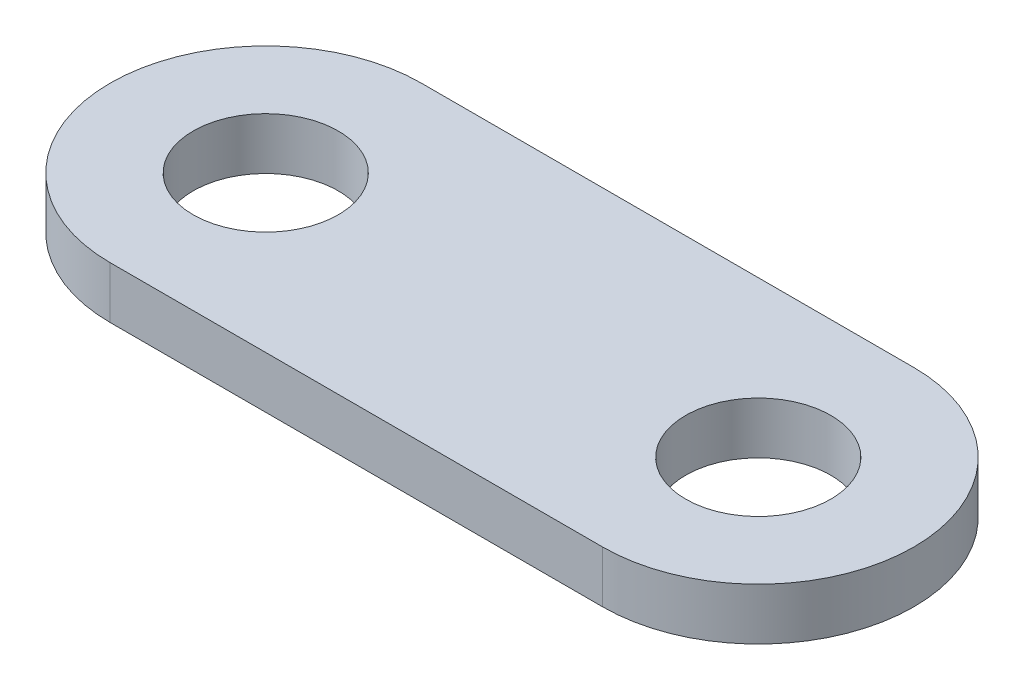
SolidWorks part; units mm, degrees
ref_plane "Front Plane" through (0, 0, 0) normal (0, 0, 1) x (1, 0, 0)
ref_plane "Top Plane" through (0, 0, 0) normal (0, 1, 0) x (1, 0, 0)
ref_plane "Right Plane" through (0, 0, 0) normal (1, 0, 0) x (0, 0, -1)
sketch "Sketch1" plane through (0, 0, 0) normal (0, 1, 0) x (1, 0, 0)
  line L0 (-23.75, 0) -> (23.75, 0) construction
  line L1 (-23.75, 15) -> (23.75, 15)
  line L2 (-23.75, -15) -> (23.75, -15)
  arc A0 (-23.75, 15) -> (-23.75, -15) centre (-23.75, 0) ccw
  arc A1 (23.75, -15) -> (23.75, 15) centre (23.75, 0) ccw
  circle A2 centre (-23.75, 0) radius 7
  circle A3 centre (23.75, 0) radius 7
  point P2 (0, 0)
  dimension "D2" = 15
  dimension "D3" = 14
  dimension "D1" = 47.5
extrude "Boss-Extrude1" add sketch "Sketch1" along normal blind 5
